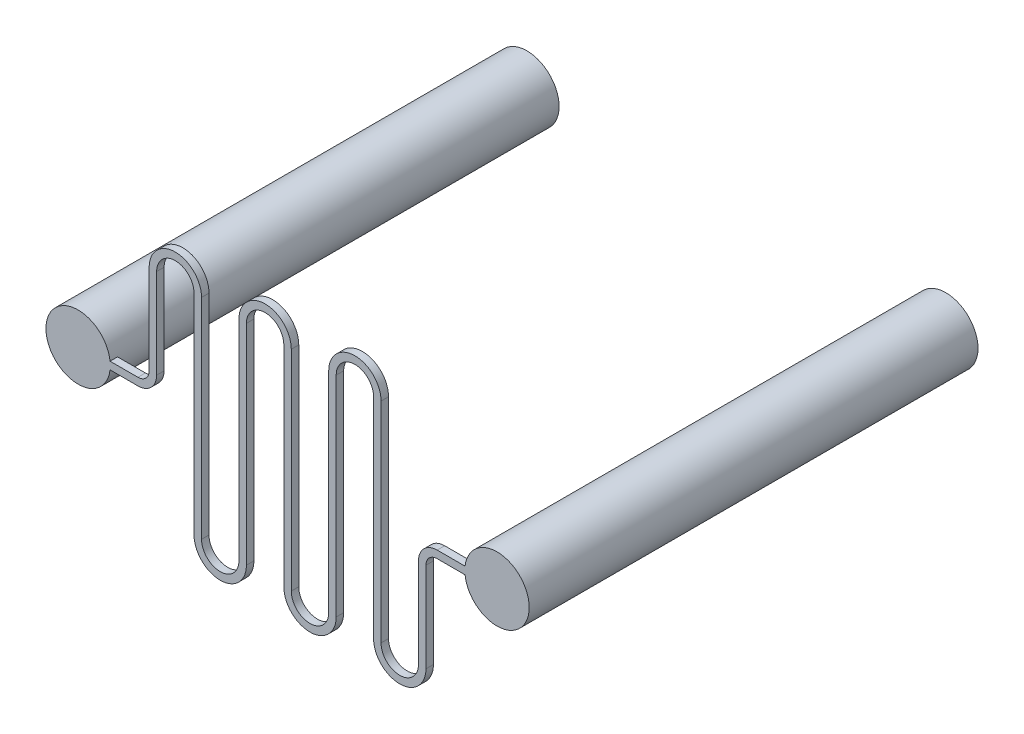
SolidWorks part; units mm, degrees
ref_plane "Front Plane" through (0, 0, 0) normal (0, 0, 1) x (1, 0, 0)
ref_plane "Top Plane" through (0, 0, 0) normal (0, 1, 0) x (1, 0, 0)
ref_plane "Right Plane" through (0, 0, 0) normal (1, 0, 0) x (0, 0, -1)
sketch "Sketch2" plane through (0, 0, 0) normal (0, 0, 1) x (1, 0, 0)
  line L3 (-17.5, -0.25) -> (-13.5, -0.25)
  line L6 (-12.25, 1) -> (-12.25, 7)
  line L9 (-9.75, 7) -> (-9.75, 0)
  line L12 (-9.75, 0) -> (-9.75, -7)
  line L15 (-6.25, -7) -> (-6.25, 0)
  line L18 (-6.25, 0) -> (-6.25, 7)
  line L21 (-3.75, 7) -> (-3.75, 0)
  line L22 (-3.75, 0) -> (-3.75, -7)
  line L23 (-0.25, -7) -> (-0.25, 0)
  line L24 (-0.25, 0) -> (-0.25, 7)
  line L25 (2.25, 7) -> (2.25, 0)
  line L26 (2.25, 0) -> (2.25, -7)
  line L27 (5.75, -7) -> (5.75, -1)
  line L28 (6.5, -0.25) -> (10.5, -0.25)
  line L29 (-17.5, 0.25) -> (-13.5, 0.25)
  line L30 (-12.75, 1) -> (-12.75, 7)
  line L31 (-9.25, 7) -> (-9.25, 0)
  line L32 (-9.25, 0) -> (-9.25, -7)
  line L33 (-6.75, -7) -> (-6.75, 0)
  line L34 (-6.75, 0) -> (-6.75, 7)
  line L35 (-3.25, 7) -> (-3.25, 0)
  line L36 (-3.25, 0) -> (-3.25, -7)
  line L37 (-0.75, -7) -> (-0.75, 0)
  line L38 (-0.75, 0) -> (-0.75, 7)
  line L39 (2.75, 7) -> (2.75, 0)
  line L40 (2.75, 0) -> (2.75, -7)
  line L41 (5.25, -7) -> (5.25, -1)
  line L42 (6.5, 0.25) -> (10.5, 0.25)
  arc A0 (-17.5, 0.25) -> (-17.5, -0.25) centre (-17.5, 0) ccw
  arc A8 (-12.25, 1) -> (-13.5, -0.25) centre (-13.5, 1) cw
  arc A9 (-12.25, 7) -> (-9.75, 7) centre (-11, 7) cw
  arc A10 (-9.75, -7) -> (-6.25, -7) centre (-8, -7) ccw
  arc A11 (-6.25, 7) -> (-3.75, 7) centre (-5, 7) cw
  arc A12 (-3.75, -7) -> (-0.25, -7) centre (-2, -7) ccw
  arc A13 (-0.25, 7) -> (2.25, 7) centre (1, 7) cw
  arc A14 (2.25, -7) -> (5.75, -7) centre (4, -7) ccw
  arc A15 (5.75, -1) -> (6.5, -0.25) centre (6.5, -1) cw
  arc A16 (-12.75, 1) -> (-13.5, 0.25) centre (-13.5, 1) cw
  arc A17 (-12.75, 7) -> (-9.25, 7) centre (-11, 7) cw
  arc A18 (-9.25, -7) -> (-6.75, -7) centre (-8, -7) ccw
  arc A19 (-6.75, 7) -> (-3.25, 7) centre (-5, 7) cw
  arc A20 (-3.25, -7) -> (-0.75, -7) centre (-2, -7) ccw
  arc A21 (-0.75, 7) -> (2.75, 7) centre (1, 7) cw
  arc A22 (2.75, -7) -> (5.25, -7) centre (4, -7) ccw
  arc A23 (5.25, -1) -> (6.5, 0.25) centre (6.5, -1) cw
  arc A24 (10.5, -0.25) -> (10.5, 0.25) centre (10.5, 0) ccw
  point P4 (0, 0)
  point P32 (5.5, 0)
  point P35 (-12.5, 0)
  dimension "D14" = 5
extrude "Boss-Extrude1" add sketch "Sketch2" along normal blind 0.5
ref_plane "Plane1" through (0, 0, 0) normal (0, -1, 0) x (-1, 0, 0)
sketch "Sketch3" plane through (0, 0, 0) normal (0, -1, 0) x (-1, 0, 0)
  line L0 (17.5, -0.5) -> (19.65, -0.5)
  line L2 (17.5, -0.5) -> (17.5, 29.5)
  line L3 (17.5, 29.5) -> (19.65, 29.5)
  line L4 (19.65, 29.5) -> (19.65, -0.5)
  dimension "D3" = 2.15
  dimension "D4" = 30
ref_plane "Plane2" through (0, 0, 0) normal (0, -1, 0) x (-1, 0, 0)
sketch "Sketch4" plane through (0, 0, 0) normal (0, -1, 0) x (-1, 0, 0)
  line L0 (-10.5, -0.5) -> (-12.65, -0.5)
  line L2 (-10.5, -0.5) -> (-10.5, 29.5)
  line L3 (-10.5, 29.5) -> (-12.65, 29.5)
  line L4 (-12.65, 29.5) -> (-12.65, -0.5)
  dimension "D3" = 30
  dimension "D4" = 2.15
revolve "Revolve1" add sketch "Sketch3" angle 360 about L2
revolve "Revolve2" add sketch "Sketch4" angle 360 about L2
sketch "Sketch5" plane through (0, 0, -29.5) normal (0, 0, -1) x (-1, 0, 0)
  circle A0 centre (-10.5, 0) radius 1.75
  circle A1 centre (17.5, 0) radius 1.75
  dimension "D1" = 3.5
  dimension "D2" = 3.5
extrude "Cut-Extrude1" cut sketch "Sketch5" against normal blind 29
